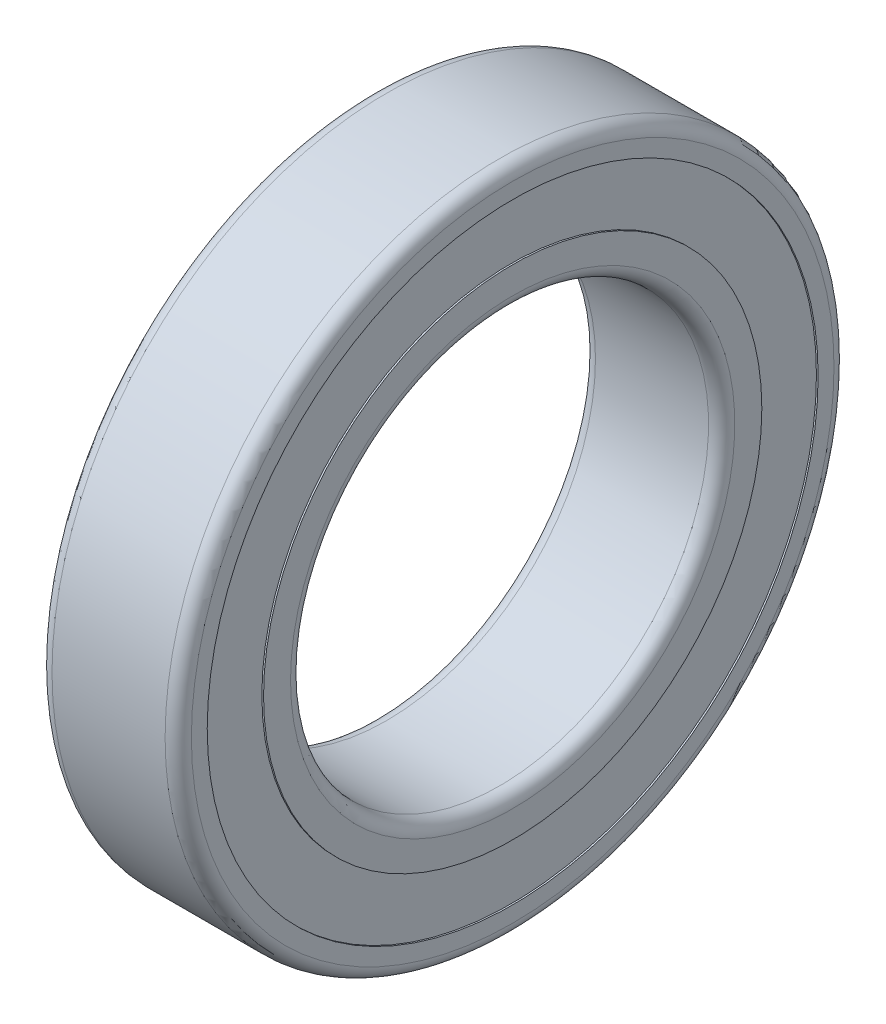
SolidWorks part; units mm, degrees
material "1.4301 (X5CrNi18-10)"
ref_plane "正面" through (0, 0, 0) normal (0, 0, 1) x (1, 0, 0)
ref_plane "平面" through (0, 0, 0) normal (0, 1, 0) x (1, 0, 0)
ref_plane "右側面" through (0, 0, 0) normal (1, 0, 0) x (0, 0, -1)
sketch "ｽｹｯﾁ1" plane through (0, 0, 0) normal (0, 0, 1) x (1, 0, 0)
  line L0 (0, 0) -> (33211.2791, 0) construction
  line L1 (-2.5, 12) -> (2.5, 12)
  line L2 (2.5, 12) -> (2.5, 10.96)
  line L3 (2.5, 10.96) -> (2.27, 10.96)
  line L4 (2.27, 10.96) -> (2.27, 10.56)
  line L5 (2.27, 10.56) -> (1.08, 10.56)
  line L6 (0, 12) -> (0, 0) construction
  line L7 (-1.08, 10.56) -> (-2.27, 10.56)
  line L8 (-2.5, 8.94) -> (-1.08, 8.94)
  line L9 (2.5, 8.94) -> (2.5, 7.5)
  line L10 (2.5, 7.5) -> (-2.5, 7.5)
  line L11 (-2.5, 8.94) -> (-2.5, 7.5)
  line L12 (-2.27, 10.96) -> (-2.27, 10.56)
  line L13 (-2.5, 10.96) -> (-2.27, 10.96)
  line L14 (-2.5, 12) -> (-2.5, 10.96)
  line L15 (1.08, 8.94) -> (2.5, 8.94)
  arc A0 (-1.08, 8.94) -> (1.08, 8.94) centre (0, 9.75) ccw
  arc A1 (1.08, 10.56) -> (-1.08, 10.56) centre (0, 9.75) ccw
  dimension "D8" = 2.7
  dimension "D1" = 24
  dimension "D2" = 21.12
  dimension "D3" = 17.88
  dimension "D4" = 15
  dimension "D5" = 5
  dimension "D6" = 21.92
  dimension "D7" = 0.23
  dimension "D9" = 9.75
revolve "回転1" add sketch "ｽｹｯﾁ1" angle 360 about L0
sketch "ｽｹｯﾁ3" plane through (0, 0, 0) normal (0, 0, 1) x (1, 0, 0)
  line L0 (2.27, 10.96) -> (2.27, 8.94)
  line L1 (1.08, 8.94) -> (2.5, 8.94) construction
  line L2 (2.27, 8.94) -> (2.44, 8.94)
  line L3 (2.44, 8.94) -> (2.44, 10.96)
  line L4 (2.44, 10.96) -> (2.27, 10.96)
  line L5 (0, 0) -> (0, -50000) construction
  line L6 (-2.44, 10.96) -> (-2.27, 10.96)
  line L7 (-2.44, 8.94) -> (-2.44, 10.96)
  line L8 (-2.27, 8.94) -> (-2.44, 8.94)
  line L9 (-2.27, 10.96) -> (-2.27, 8.94)
  dimension "D1" = 0.17
revolve "回転3" add sketch "ｽｹｯﾁ3" angle 360 about L0
sketch "ｽｹｯﾁ2" plane through (0, 0, 0) normal (0, 0, 1) x (1, 0, 0)
  line L0 (0.0469, 9.75) -> (50000.0469, 9.75) construction
  line L1 (-1.3275, 9.75) -> (1.3275, 9.75)
  arc A0 (1.3275, 9.75) -> (-1.3275, 9.75) centre (0, 9.75) ccw
  dimension "D1" = 2.655
revolve "回転2" add sketch "ｽｹｯﾁ2" angle 360 about L0
pattern_circular "円形ﾊﾟﾀｰﾝ2" count 13 over 360 about axis through (0, 0, 0) along (1, 0, 0) of bodies 103
fillet "ﾌｨﾚｯﾄ1" radius 0.4712 2 edges at (2.5, 0, 12) (-2.5, 0, 12)
fillet "ﾌｨﾚｯﾄ2" radius 0.4712 2 edges at (-2.5, 0, 7.5) (2.5, 0, 7.5)
